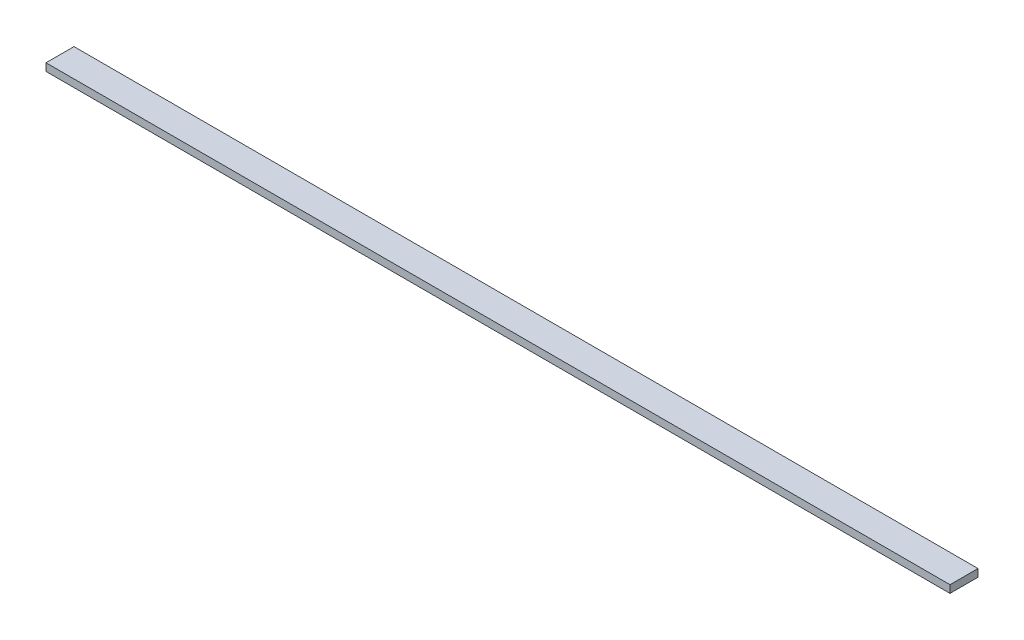
SolidWorks part; units mm, degrees
ref_plane "Front Plane" through (0, 0, 0) normal (0, 0, 1) x (1, 0, 0)
ref_plane "Top Plane" through (0, 0, 0) normal (0, 1, 0) x (1, 0, 0)
ref_plane "Right Plane" through (0, 0, 0) normal (1, 0, 0) x (0, 0, -1)
sketch "Sketch2" plane through (0, 0, 0) normal (1, 0, 0) x (0, 0, -1)
  line L1 (-10, 0) -> (0, 0)
  line L2 (-10, 0) -> (-10, 2.7)
  line L3 (-10, 2.7) -> (0, 2.7)
  line L4 (0, 0) -> (0, 2.7)
  dimension "D1" = 10
  dimension "D2" = 2.7
extrude "Boss-Extrude1" add sketch "Sketch2" along normal up to vertex (161.5 mm away) and the other way up to vertex (161.5 mm away)
